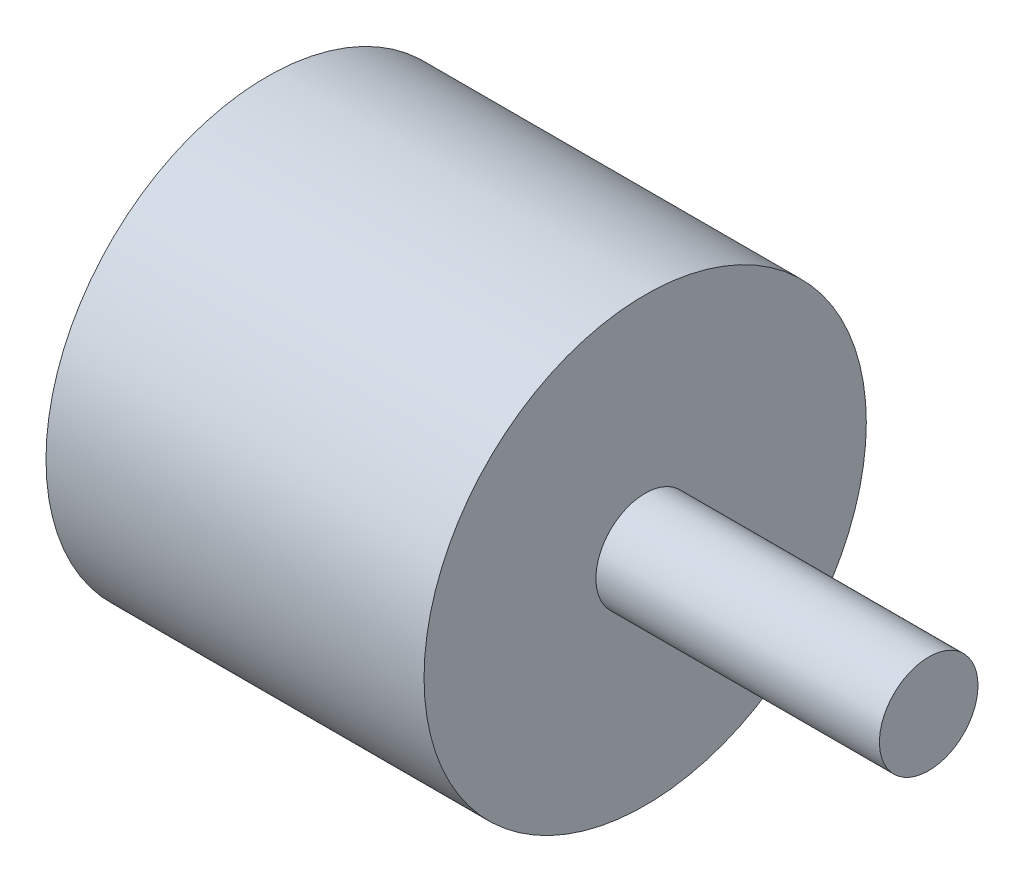
SolidWorks part; units mm, degrees
ref_plane "Front Plane" through (0, 0, 0) normal (0, 0, 1) x (1, 0, 0)
ref_plane "Top Plane" through (0, 0, 0) normal (0, 1, 0) x (1, 0, 0)
ref_plane "Right Plane" through (0, 0, 0) normal (1, 0, 0) x (0, 0, -1)
sketch "Sketch1" plane through (0, 0, 0) normal (1, 0, 0) x (0, 0, -1)
  circle A0 centre (0, 0) radius 23.3971
extrude "Boss-Extrude1" add sketch "Sketch1" along normal blind 40
sketch "Sketch2" plane through (40, 0, 0) normal (1, 0, 0) x (0, 0, -1)
  circle A0 centre (0, 0) radius 5.2143
extrude "Boss-Extrude2" add sketch "Sketch2" along normal blind 30
